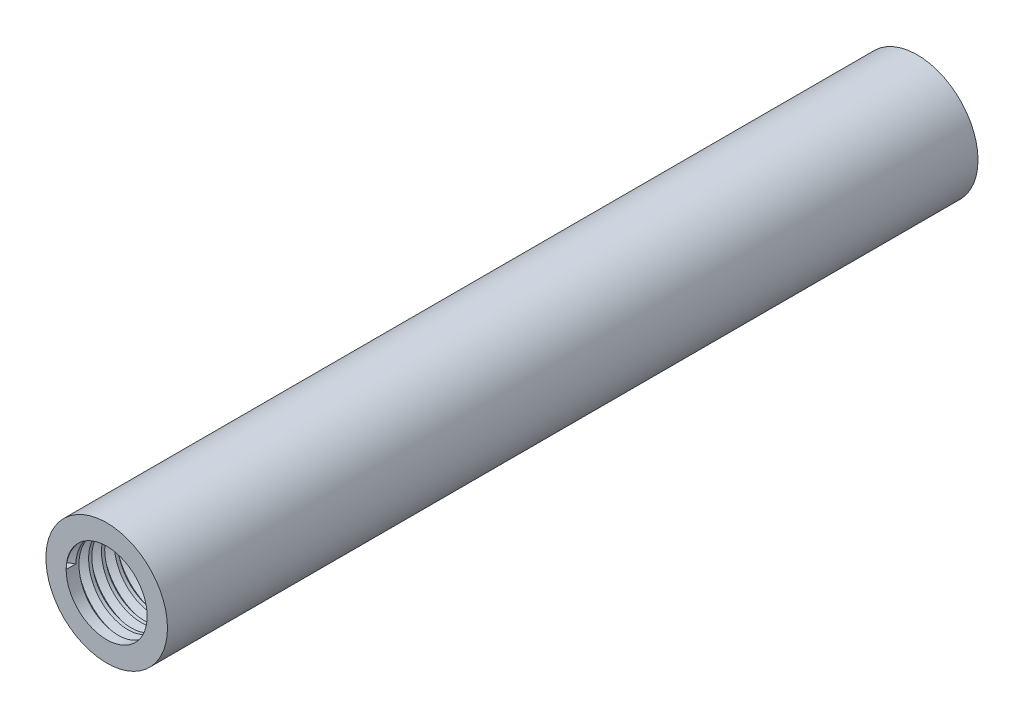
SolidWorks part; units mm, degrees
ref_plane "Front Plane" through (0, 0, 0) normal (0, 0, 1) x (1, 0, 0)
ref_plane "Top Plane" through (0, 0, 0) normal (0, 1, 0) x (1, 0, 0)
ref_plane "Right Plane" through (0, 0, 0) normal (1, 0, 0) x (0, 0, -1)
sketch "Sketch1" plane through (0, 0, 0) normal (0, 1, 0) x (1, 0, 0)
  line L0 (0, 0) -> (0, 20) construction
  line L1 (1, 20) -> (1, 15)
  line L2 (1, 15) -> (0, 15)
  line L3 (0, 15) -> (0, 5)
  line L4 (0, 5) -> (1, 5)
  line L5 (1, 5) -> (1, 0)
  line L6 (1, 0) -> (1.5, 0)
  line L7 (1.5, 0) -> (1.5, 20)
  line L8 (1.5, 20) -> (1, 20)
  dimension "D1" = 20
  dimension "D2" = 3
  dimension "D3" = 2
  dimension "D4" = 5
revolve "Revolve1" add sketch "Sketch1" angle 360 about L0
thread "Thread1" pitch 0.3175 profile "Thread Profile1" start angle 0, offset 0, length 4, pitch 0.3175, diameter 2
ref_plane "Plane1" through (-1, 0, 0) normal (0, -1, 0) x (-1, 0, 0)
sketch "Thread Profile1" plane through (-1, 0, 0) normal (0, -1, 0) x (-1, 0, 0)
  line L0 (0, 0) -> (0, 0.3175) construction
  line L1 (0, 0) -> (0.1719, 0.0992)
  line L2 (0.1719, 0.0992) -> (0.1719, 0.1389)
  line L3 (0.1719, 0.1389) -> (0, 0.2381)
  line L4 (0.1719, 0.1191) -> (0, 0.1191) construction
  line L11 (0, 0) -> (0, 0.2381)
  point P2 (0, 0)
  dimension "Pitch" = 0.3175
  dimension "Profile_Angle" = 60
  dimension "Profile_Land" = 0.0397
  dimension "Profile_Height" = 0.1719
thread "Thread2" pitch 0.3175 profile "Thread Profile2" start angle 0, offset 0, length 4, pitch 0.3175, diameter 2
ref_plane "Plane2" through (1, 0, -20) normal (0, -1, 0) x (1, 0, 0)
sketch "Thread Profile2" plane through (1, 0, -20) normal (0, -1, 0) x (1, 0, 0)
  line L0 (0, 0) -> (0, 0.3175) construction
  line L1 (0, 0) -> (0.1719, 0.0992)
  line L2 (0.1719, 0.0992) -> (0.1719, 0.1389)
  line L3 (0.1719, 0.1389) -> (0, 0.2381)
  line L4 (0.1719, 0.1191) -> (0, 0.1191) construction
  line L11 (0, 0) -> (0, 0.2381)
  point P2 (0, 0)
  dimension "Pitch" = 0.3175
  dimension "Profile_Angle" = 60
  dimension "Profile_Land" = 0.0397
  dimension "Profile_Height" = 0.1719
